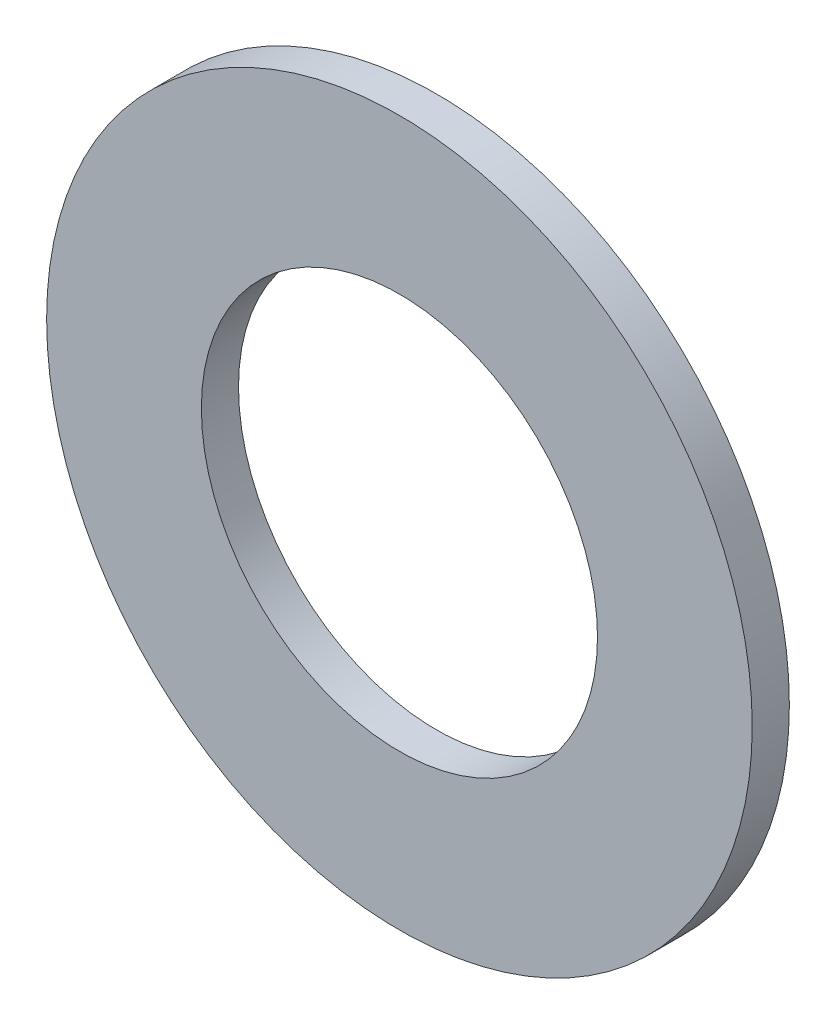
SolidWorks part; units mm, degrees
material "Delrin 2700 NC010, Low Viscosity Acetal Copolymer (SS)"
ref_plane "Front Plane" through (0, 0, 0) normal (0, 0, 1) x (1, 0, 0)
ref_plane "Top Plane" through (0, 0, 0) normal (0, 1, 0) x (1, 0, 0)
ref_plane "Right Plane" through (0, 0, 0) normal (1, 0, 0) x (0, 0, -1)
sketch "Sketch1" plane through (0, 0, 0) normal (0, 0, 1) x (1, 0, 0)
  circle A0 centre (0, 0) radius 7.239
  circle A1 centre (0, 0) radius 4.064
  dimension "D1" = 8.128
  dimension "D2" = 14.478
extrude "Boss-Extrude1" add sketch "Sketch1" along normal blind 0.762
